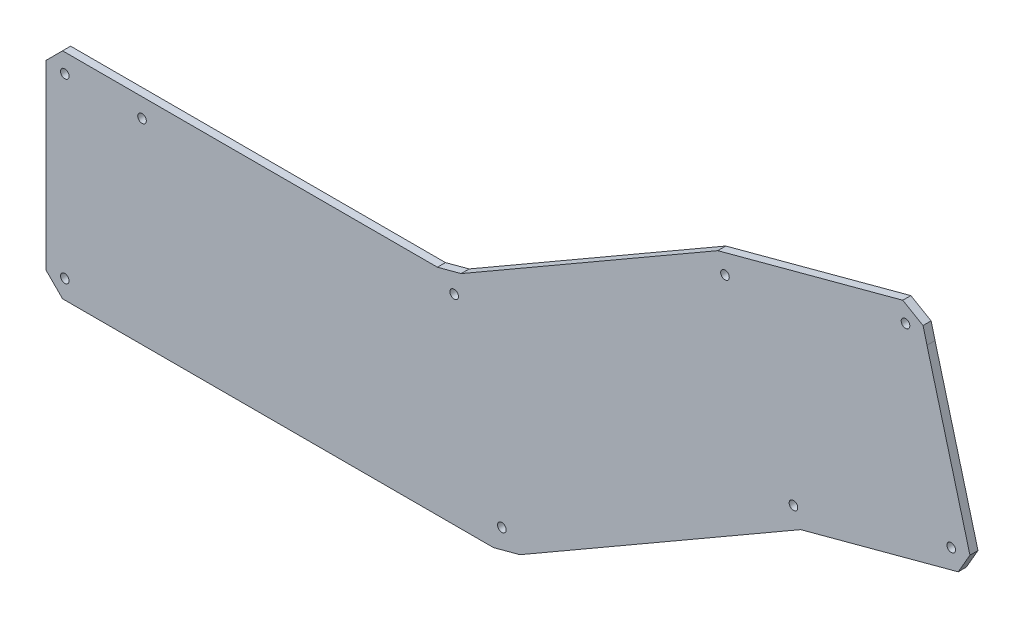
SolidWorks part; units mm, degrees
ref_plane "Plan de face" through (0, 0, 0) normal (0, 0, 1) x (1, 0, 0)
ref_plane "Plan de dessus" through (0, 0, 0) normal (0, 1, 0) x (1, 0, 0)
ref_plane "Plan de droite" through (0, 0, 0) normal (1, 0, 0) x (0, 0, -1)
sketch "Esquisse1" plane through (0, 0, 0) normal (0, 0, 1) x (1, 0, 0)
  line L0 (-73.9886, 18.0851) -> (-59.9886, 18.0851) construction
  line L1 (-73.9886, 37.0851) -> (-59.9886, 37.0851) construction
  line L2 (-73.9886, 37.0851) -> (-73.9886, 23.0851) construction
  line L3 (-73.9886, 23.0851) -> (-59.9886, 23.0851) construction
  line L4 (-59.9886, 37.0851) -> (-59.9886, 23.0851) construction
  line L5 (-73.9886, 18.0851) -> (-73.9886, 4.0851) construction
  line L6 (-73.9886, 4.0851) -> (-59.9886, 4.0851) construction
  line L7 (-59.9886, 18.0851) -> (-59.9886, 4.0851) construction
  line L8 (-73.9886, -0.9149) -> (-59.9886, -0.9149) construction
  line L9 (-73.9886, -0.9149) -> (-73.9886, -14.9149) construction
  line L10 (-73.9886, -14.9149) -> (-59.9886, -14.9149) construction
  line L11 (-59.9886, -0.9149) -> (-59.9886, -14.9149) construction
  line L12 (-73.9886, 37.0851) -> (-73.9886, 18.0851) construction
  line L13 (-54.9886, 18.0851) -> (-40.9886, 18.0851) construction
  line L14 (-54.9886, 37.0851) -> (-40.9886, 37.0851) construction
  line L15 (-54.9886, 37.0851) -> (-54.9886, 23.0851) construction
  line L16 (-54.9886, 23.0851) -> (-40.9886, 23.0851) construction
  line L17 (-40.9886, 37.0851) -> (-40.9886, 23.0851) construction
  line L18 (-54.9886, 18.0851) -> (-54.9886, 4.0851) construction
  line L19 (-54.9886, 4.0851) -> (-40.9886, 4.0851) construction
  line L20 (-40.9886, 18.0851) -> (-40.9886, 4.0851) construction
  line L21 (-54.9886, -0.9149) -> (-40.9886, -0.9149) construction
  line L22 (-54.9886, -0.9149) -> (-54.9886, -14.9149) construction
  line L23 (-54.9886, -14.9149) -> (-40.9886, -14.9149) construction
  line L24 (-40.9886, -0.9149) -> (-40.9886, -14.9149) construction
  line L25 (-54.9886, 37.0851) -> (-54.9886, 18.0851) construction
  line L26 (-35.9886, 18.0851) -> (-21.9886, 18.0851) construction
  line L27 (-35.9886, 37.0851) -> (-21.9886, 37.0851) construction
  line L28 (-35.9886, 37.0851) -> (-35.9886, 23.0851) construction
  line L29 (-35.9886, 23.0851) -> (-21.9886, 23.0851) construction
  line L30 (-21.9886, 37.0851) -> (-21.9886, 23.0851) construction
  line L31 (-35.9886, 18.0851) -> (-35.9886, 4.0851) construction
  line L32 (-35.9886, 4.0851) -> (-21.9886, 4.0851) construction
  line L33 (-21.9886, 18.0851) -> (-21.9886, 4.0851) construction
  line L34 (-35.9886, -0.9149) -> (-21.9886, -0.9149) construction
  line L35 (-35.9886, -0.9149) -> (-35.9886, -14.9149) construction
  line L36 (-35.9886, -14.9149) -> (-21.9886, -14.9149) construction
  line L37 (-21.9886, -0.9149) -> (-21.9886, -14.9149) construction
  line L38 (-35.9886, 37.0851) -> (-35.9886, 18.0851) construction
  line L39 (-16.9886, 18.0851) -> (-2.9886, 18.0851) construction
  line L40 (-16.9886, 37.0851) -> (-2.9886, 37.0851) construction
  line L41 (-16.9886, 37.0851) -> (-16.9886, 23.0851) construction
  line L42 (-16.9886, 23.0851) -> (-2.9886, 23.0851) construction
  line L43 (-2.9886, 37.0851) -> (-2.9886, 23.0851) construction
  line L44 (-16.9886, 18.0851) -> (-16.9886, 4.0851) construction
  line L45 (-16.9886, 4.0851) -> (-2.9886, 4.0851) construction
  line L46 (-2.9886, 18.0851) -> (-2.9886, 4.0851) construction
  line L47 (-16.9886, -0.9149) -> (-2.9886, -0.9149) construction
  line L48 (-16.9886, -0.9149) -> (-16.9886, -14.9149) construction
  line L49 (-16.9886, -14.9149) -> (-2.9886, -14.9149) construction
  line L50 (-2.9886, -0.9149) -> (-2.9886, -14.9149) construction
  line L51 (-16.9886, 37.0851) -> (-16.9886, 18.0851) construction
  line L52 (2.0114, 18.0851) -> (16.0114, 18.0851) construction
  line L53 (2.0114, 37.0851) -> (16.0114, 37.0851) construction
  line L54 (2.0114, 37.0851) -> (2.0114, 23.0851) construction
  line L55 (2.0114, 23.0851) -> (16.0114, 23.0851) construction
  line L56 (16.0114, 37.0851) -> (16.0114, 23.0851) construction
  line L57 (2.0114, 18.0851) -> (2.0114, 4.0851) construction
  line L58 (2.0114, 4.0851) -> (16.0114, 4.0851) construction
  line L59 (16.0114, 18.0851) -> (16.0114, 4.0851) construction
  line L60 (2.0114, -0.9149) -> (16.0114, -0.9149) construction
  line L61 (2.0114, -0.9149) -> (2.0114, -14.9149) construction
  line L62 (2.0114, -14.9149) -> (16.0114, -14.9149) construction
  line L63 (16.0114, -0.9149) -> (16.0114, -14.9149) construction
  line L64 (2.0114, 37.0851) -> (2.0114, 18.0851) construction
  line L65 (21.0114, 18.0851) -> (35.0114, 18.0851) construction
  line L66 (21.0114, 37.0851) -> (35.0114, 37.0851) construction
  line L67 (21.0114, 37.0851) -> (21.0114, 23.0851) construction
  line L68 (21.0114, 23.0851) -> (35.0114, 23.0851) construction
  line L69 (35.0114, 37.0851) -> (35.0114, 23.0851) construction
  line L70 (21.0114, 18.0851) -> (21.0114, 4.0851) construction
  line L71 (21.0114, 4.0851) -> (35.0114, 4.0851) construction
  line L72 (35.0114, 18.0851) -> (35.0114, 4.0851) construction
  line L73 (21.0114, -0.9149) -> (35.0114, -0.9149) construction
  line L74 (21.0114, -0.9149) -> (21.0114, -14.9149) construction
  line L75 (21.0114, -14.9149) -> (35.0114, -14.9149) construction
  line L76 (35.0114, -0.9149) -> (35.0114, -14.9149) construction
  line L77 (21.0114, 37.0851) -> (21.0114, 18.0851) construction
  line L78 (40.0114, 18.0851) -> (54.0114, 18.0851) construction
  line L79 (40.0114, 37.0851) -> (54.0114, 37.0851) construction
  line L80 (40.0114, 37.0851) -> (40.0114, 23.0851) construction
  line L81 (40.0114, 23.0851) -> (54.0114, 23.0851) construction
  line L82 (54.0114, 37.0851) -> (54.0114, 23.0851) construction
  line L83 (40.0114, 18.0851) -> (40.0114, 4.0851) construction
  line L84 (40.0114, 4.0851) -> (54.0114, 4.0851) construction
  line L85 (54.0114, 18.0851) -> (54.0114, 4.0851) construction
  line L86 (40.0114, -0.9149) -> (54.0114, -0.9149) construction
  line L87 (40.0114, -0.9149) -> (40.0114, -14.9149) construction
  line L88 (40.0114, -14.9149) -> (54.0114, -14.9149) construction
  line L89 (54.0114, -0.9149) -> (54.0114, -14.9149) construction
  line L90 (40.0114, 37.0851) -> (40.0114, 18.0851) construction
  line L91 (-73.9886, 18.0851) -> (-54.9886, 18.0851) construction
  line L92 (56.0114, 20.0851) -> (56.7532, 18.8002) construction
  line L93 (38.0114, 39.0851) -> (56.0114, 39.0851) construction
  line L94 (56.0114, 39.0851) -> (56.0114, 21.0851) construction
  line L95 (38.0114, 21.0851) -> (56.0114, 21.0851) construction
  line L96 (38.0114, 39.0851) -> (38.0114, 21.0851) construction
  line L97 (19.0114, 39.0851) -> (37.0114, 39.0851) construction
  line L98 (37.0114, 39.0851) -> (37.0114, 21.0851) construction
  line L99 (19.0114, 21.0851) -> (37.0114, 21.0851) construction
  line L100 (19.0114, 39.0851) -> (19.0114, 21.0851) construction
  line L101 (79.4363, 55.512) -> (88.4363, 39.9235) construction
  line L102 (88.4363, 39.9235) -> (72.8478, 30.9235) construction
  line L103 (63.8478, 46.512) -> (72.8478, 30.9235) construction
  line L104 (79.4363, 55.512) -> (63.8478, 46.512) construction
  line L105 (62.9818, 46.012) -> (71.9818, 30.4235) construction
  line L106 (71.9818, 30.4235) -> (56.3933, 21.4235) construction
  line L107 (47.3933, 37.012) -> (56.3933, 21.4235) construction
  line L108 (62.9818, 46.012) -> (47.3933, 37.012) construction
  line L109 (164.2542, 60.603) -> (148.6657, 51.603) construction
  line L110 (62.2497, 43.2799) -> (71.7497, 26.8254) construction
  line L111 (78.7042, 52.7799) -> (88.2042, 36.3254) construction
  line L112 (95.1587, 62.2799) -> (104.6587, 45.8254) construction
  line L113 (111.6132, 71.7799) -> (121.1132, 55.3254) construction
  line L114 (128.0677, 81.2799) -> (137.5677, 64.8254) construction
  line L115 (144.5221, 90.7799) -> (154.0221, 74.3254) construction
  line L116 (148.6657, 51.603) -> (157.6657, 36.0146) construction
  line L117 (69.1254, 3.371) -> (76.1254, -8.7534) construction
  line L118 (88.2497, -1.7534) -> (76.1254, -8.7534) construction
  line L119 (81.2497, 10.371) -> (88.2497, -1.7534) construction
  line L120 (81.2497, 10.371) -> (69.1254, 3.371) construction
  line L121 (59.6254, 19.8254) -> (66.6254, 7.7011) construction
  line L122 (78.7497, 14.7011) -> (66.6254, 7.7011) construction
  line L123 (71.7497, 26.8254) -> (78.7497, 14.7011) construction
  line L124 (50.1254, 36.2799) -> (57.1254, 24.1556) construction
  line L125 (69.2497, 31.1556) -> (57.1254, 24.1556) construction
  line L126 (62.2497, 43.2799) -> (69.2497, 31.1556) construction
  line L127 (62.2497, 43.2799) -> (50.1254, 36.2799) construction
  line L128 (71.7497, 26.8254) -> (59.6254, 19.8254) construction
  line L129 (85.5799, 12.871) -> (92.5799, 0.7466) construction
  line L130 (104.7042, 7.7466) -> (92.5799, 0.7466) construction
  line L131 (97.7042, 19.871) -> (104.7042, 7.7466) construction
  line L132 (97.7042, 19.871) -> (85.5799, 12.871) construction
  line L133 (76.0799, 29.3254) -> (83.0799, 17.2011) construction
  line L134 (95.2042, 24.2011) -> (83.0799, 17.2011) construction
  line L135 (88.2042, 36.3254) -> (95.2042, 24.2011) construction
  line L136 (66.5799, 45.7799) -> (73.5799, 33.6556) construction
  line L137 (85.7042, 40.6556) -> (73.5799, 33.6556) construction
  line L138 (78.7042, 52.7799) -> (85.7042, 40.6556) construction
  line L139 (78.7042, 52.7799) -> (66.5799, 45.7799) construction
  line L140 (88.2042, 36.3254) -> (76.0799, 29.3254) construction
  line L141 (102.0343, 22.371) -> (109.0343, 10.2466) construction
  line L142 (121.1587, 17.2466) -> (109.0343, 10.2466) construction
  line L143 (114.1587, 29.371) -> (121.1587, 17.2466) construction
  line L144 (114.1587, 29.371) -> (102.0343, 22.371) construction
  line L145 (92.5343, 38.8254) -> (99.5343, 26.7011) construction
  line L146 (111.6587, 33.7011) -> (99.5343, 26.7011) construction
  line L147 (104.6587, 45.8254) -> (111.6587, 33.7011) construction
  line L148 (83.0343, 55.2799) -> (90.0343, 43.1556) construction
  line L149 (102.1587, 50.1556) -> (90.0343, 43.1556) construction
  line L150 (95.1587, 62.2799) -> (102.1587, 50.1556) construction
  line L151 (95.1587, 62.2799) -> (83.0343, 55.2799) construction
  line L152 (104.6587, 45.8254) -> (92.5343, 38.8254) construction
  line L153 (118.4888, 31.871) -> (125.4888, 19.7466) construction
  line L154 (137.6132, 26.7466) -> (125.4888, 19.7466) construction
  line L155 (130.6132, 38.871) -> (137.6132, 26.7466) construction
  line L156 (130.6132, 38.871) -> (118.4888, 31.871) construction
  line L157 (108.9888, 48.3254) -> (115.9888, 36.2011) construction
  line L158 (128.1132, 43.2011) -> (115.9888, 36.2011) construction
  line L159 (121.1132, 55.3254) -> (128.1132, 43.2011) construction
  line L160 (99.4888, 64.7799) -> (106.4888, 52.6556) construction
  line L161 (118.6132, 59.6556) -> (106.4888, 52.6556) construction
  line L162 (111.6132, 71.7799) -> (118.6132, 59.6556) construction
  line L163 (111.6132, 71.7799) -> (99.4888, 64.7799) construction
  line L164 (121.1132, 55.3254) -> (108.9888, 48.3254) construction
  line L165 (134.9433, 41.371) -> (141.9433, 29.2466) construction
  line L166 (154.0677, 36.2466) -> (141.9433, 29.2466) construction
  line L167 (147.0677, 48.371) -> (154.0677, 36.2466) construction
  line L168 (147.0677, 48.371) -> (134.9433, 41.371) construction
  line L169 (125.4433, 57.8254) -> (132.4433, 45.7011) construction
  line L170 (144.5677, 52.7011) -> (132.4433, 45.7011) construction
  line L171 (137.5677, 64.8254) -> (144.5677, 52.7011) construction
  line L172 (115.9433, 74.2799) -> (122.9433, 62.1556) construction
  line L173 (135.0677, 69.1556) -> (122.9433, 62.1556) construction
  line L174 (128.0677, 81.2799) -> (135.0677, 69.1556) construction
  line L175 (128.0677, 81.2799) -> (115.9433, 74.2799) construction
  line L176 (137.5677, 64.8254) -> (125.4433, 57.8254) construction
  line L177 (151.3978, 50.871) -> (158.3978, 38.7466) construction
  line L178 (170.5221, 45.7466) -> (158.3978, 38.7466) construction
  line L179 (163.5221, 57.871) -> (170.5221, 45.7466) construction
  line L180 (163.5221, 57.871) -> (151.3978, 50.871) construction
  line L181 (141.8978, 67.3254) -> (148.8978, 55.2011) construction
  line L182 (161.0221, 62.2011) -> (148.8978, 55.2011) construction
  line L183 (154.0221, 74.3254) -> (161.0221, 62.2011) construction
  line L184 (132.3978, 83.7799) -> (139.3978, 71.6556) construction
  line L185 (151.5221, 78.6556) -> (139.3978, 71.6556) construction
  line L186 (144.5221, 90.7799) -> (151.5221, 78.6556) construction
  line L187 (144.5221, 90.7799) -> (132.3978, 83.7799) construction
  line L188 (154.0221, 74.3254) -> (141.8978, 67.3254) construction
  line L189 (173.2542, 45.0146) -> (157.6657, 36.0146) construction
  line L190 (164.2542, 60.603) -> (173.2542, 45.0146) construction
  line L191 (178.3169, 34.0986) -> (169.0534, 56.4627) construction
  line L192 (169.5193, 62.7839) -> (174.1781, 45.3972) construction
  line L193 (174.1781, 45.3972) -> (191.5647, 50.056) construction
  line L194 (186.906, 67.4426) -> (191.5647, 50.056) construction
  line L195 (162.1337, 98.0749) -> (167.0513, 79.7223) construction
  line L196 (169.5193, 62.7839) -> (186.906, 67.4426) construction
  line L197 (167.0513, 79.7223) -> (180.5742, 83.3457) construction
  line L198 (162.1337, 98.0749) -> (175.6567, 101.6983) construction
  line L199 (162.1337, 98.0749) -> (165.7572, 84.5519) construction
  line L200 (165.7572, 84.5519) -> (179.2801, 88.1754) construction
  line L201 (175.6567, 101.6983) -> (179.2801, 88.1754) construction
  line L202 (167.0513, 79.7223) -> (170.6747, 66.1993) construction
  line L203 (170.6747, 66.1993) -> (184.1977, 69.8228) construction
  line L204 (180.5742, 83.3457) -> (184.1977, 69.8228) construction
  line L205 (171.9688, 61.3697) -> (185.4918, 64.9932) construction
  line L206 (171.9688, 61.3697) -> (175.5923, 47.8467) construction
  line L207 (175.5923, 47.8467) -> (189.1152, 51.4702) construction
  line L208 (185.4918, 64.9932) -> (189.1152, 51.4702) construction
  line L209 (185.4038, 84.6398) -> (198.9268, 88.2633) construction
  line L210 (180.4863, 102.9924) -> (194.0092, 106.6159) construction
  line L211 (180.4863, 102.9924) -> (184.1097, 89.4695) construction
  line L212 (184.1097, 89.4695) -> (197.6327, 93.0929) construction
  line L213 (194.0092, 106.6159) -> (197.6327, 93.0929) construction
  line L214 (185.4038, 84.6398) -> (189.0273, 71.1169) construction
  line L215 (189.0273, 71.1169) -> (202.5503, 74.7403) construction
  line L216 (198.9268, 88.2633) -> (202.5503, 74.7403) construction
  line L217 (190.3214, 66.2873) -> (203.8444, 69.9107) construction
  line L218 (190.3214, 66.2873) -> (193.9449, 52.7643) construction
  line L219 (193.9449, 52.7643) -> (207.4678, 56.3878) construction
  line L220 (203.8444, 69.9107) -> (207.4678, 56.3878) construction
  line L221 (187.8719, 67.7015) -> (192.5307, 50.3148) construction
  line L222 (192.5307, 50.3148) -> (209.9173, 54.9735) construction
  line L223 (205.2586, 72.3602) -> (209.9173, 54.9735) construction
  line L224 (180.4863, 102.9924) -> (185.4038, 84.6398) construction
  line L225 (187.8719, 67.7015) -> (205.2586, 72.3602) construction
  line L226 (203.7564, 89.5574) -> (217.2794, 93.1809) construction
  line L227 (198.8389, 107.91) -> (212.3618, 111.5335) construction
  line L228 (198.8389, 107.91) -> (202.4623, 94.387) construction
  line L229 (202.4623, 94.387) -> (215.9853, 98.0105) construction
  line L230 (212.3618, 111.5335) -> (215.9853, 98.0105) construction
  line L231 (203.7564, 89.5574) -> (207.3799, 76.0344) construction
  line L232 (207.3799, 76.0344) -> (220.9029, 79.6579) construction
  line L233 (217.2794, 93.1809) -> (220.9029, 79.6579) construction
  line L234 (208.674, 71.2048) -> (222.197, 74.8283) construction
  line L235 (208.674, 71.2048) -> (212.2975, 57.6819) construction
  line L236 (212.2975, 57.6819) -> (225.8204, 61.3053) construction
  line L237 (222.197, 74.8283) -> (225.8204, 61.3053) construction
  line L238 (206.2245, 72.619) -> (210.8833, 55.2324) construction
  line L239 (210.8833, 55.2324) -> (228.2699, 59.8911) construction
  line L240 (223.6112, 77.2778) -> (228.2699, 59.8911) construction
  line L241 (198.8389, 107.91) -> (203.7564, 89.5574) construction
  line L242 (206.2245, 72.619) -> (223.6112, 77.2778) construction
  line L243 (167.0513, 79.7223) -> (185.4038, 84.6398) construction
  line L244 (38.0114, 20.0851) -> (56.0114, 20.0851) construction
  line L245 (56.0114, 20.0851) -> (56.0114, 2.0851) construction
  line L246 (38.0114, 2.0851) -> (56.0114, 2.0851) construction
  line L247 (38.0114, 20.0851) -> (38.0114, 2.0851) construction
  line L248 (72.4818, 29.5575) -> (56.8933, 20.5575) construction
  line L249 (56.8933, 20.5575) -> (65.8933, 4.969) construction
  line L250 (81.4818, 13.969) -> (65.8933, 4.969) construction
  line L251 (72.4818, 29.5575) -> (81.4818, 13.969) construction
  line L252 (56.8933, 20.5575) -> (57.6111, 19.3142) construction
  line L253 (164.6018, 81.1365) -> (169.2605, 63.7498) construction
  line L254 (169.2605, 63.7498) -> (186.6472, 68.4086) construction
  line L255 (181.9884, 85.7952) -> (186.6472, 68.4086) construction
  line L256 (164.6018, 81.1365) -> (181.9884, 85.7952) construction
  line L257 (154.7542, 77.0575) -> (163.7542, 61.469) construction
  line L258 (163.7542, 61.469) -> (148.1657, 52.469) construction
  line L259 (139.1657, 68.0575) -> (148.1657, 52.469) construction
  line L260 (154.7542, 77.0575) -> (139.1657, 68.0575) construction
  line L261 (196.3894, 109.3242) -> (213.776, 113.983) construction
  line L262 (-94.7538, 35.7952) -> (-76.7538, 35.7952) construction
  line L263 (-94.7538, 35.7952) -> (-94.7538, 2.7952) construction
  line L264 (-94.7538, 2.7952) -> (-76.7538, 2.7952) construction
  line L265 (-76.7538, 35.7952) -> (-76.7538, 2.7952) construction
  line L266 (213.776, 113.983) -> (218.4348, 96.5963) construction
  line L267 (201.0481, 91.9375) -> (218.4348, 96.5963) construction
  line L268 (196.3894, 109.3242) -> (201.0481, 91.9375) construction
  line L269 (-75.9886, -16.9149) -> (-57.9886, -16.9149) construction
  line L270 (-57.9886, 1.0851) -> (-57.9886, -16.9149) construction
  line L271 (-75.9886, 1.0851) -> (-57.9886, 1.0851) construction
  line L272 (-75.9886, 1.0851) -> (-75.9886, -16.9149) construction
  line L273 (38.0114, -16.9149) -> (56.0114, -16.9149) construction
  line L274 (56.0114, 1.0851) -> (56.0114, -16.9149) construction
  line L275 (38.0114, 1.0851) -> (56.0114, 1.0851) construction
  line L276 (38.0114, 1.0851) -> (38.0114, -16.9149) construction
  line L277 (-75.9886, 39.0851) -> (-57.9886, 39.0851) construction
  line L278 (-57.9886, 39.0851) -> (-57.9886, 21.0851) construction
  line L279 (-75.9886, 21.0851) -> (-57.9886, 21.0851) construction
  line L280 (-75.9886, 39.0851) -> (-75.9886, 21.0851) construction
  line L281 (145.2542, 93.512) -> (129.6657, 84.512) construction
  line L282 (129.6657, 84.512) -> (138.6657, 68.9235) construction
  line L283 (154.2542, 77.9235) -> (138.6657, 68.9235) construction
  line L284 (145.2542, 93.512) -> (154.2542, 77.9235) construction
  line L285 (223.4353, 116.5711) -> (228.0941, 99.1845) construction
  line L286 (148.2159, 106.7689) -> (211.1879, 123.6422) construction
  line L287 (177.5508, 35.9482) -> (235.6877, 51.5259) construction
  line L288 (177.5508, 35.9482) -> (72.9989, -24.4149) construction
  line L289 (-95.7538, -26.9149) -> (63.6687, -26.9149) construction
  line L290 (-100.7538, 35.7952) -> (-100.7538, -21.9149) construction
  line L291 (-75.9886, 49.0851) -> (43.3046, 49.0851) construction
  line L292 (148.2159, 106.7689) -> (52.6347, 51.5851) construction
  line L293 (-75.9886, 49.0851) -> (-57.9886, 49.0851) construction
  line L294 (140.2542, 102.1722) -> (124.6657, 93.1722) construction
  line L295 (193.8012, 118.9835) -> (211.1879, 123.6422) construction
  line L296 (213.4714, 45.5731) -> (230.8581, 50.2318) construction
  line L297 (38.0114, -26.9149) -> (38.0114, -85.4624) construction
  line L298 (178.2542, 36.3543) -> (162.6657, 27.3543) construction
  line L299 (38.0114, -26.9149) -> (56.0114, -26.9149) construction
  line L300 (-100.7538, 2.7952) -> (-100.7538, -38.0419) construction
  line L301 (-100.7538, 35.7952) -> (-100.7538, 2.7952) construction
  line L302 (-75.9886, 49.0851) -> (-95.7538, 49.0851) construction
  line L303 (-100.7538, 44.0851) -> (-100.7538, 35.7952) construction
  line L304 (211.1879, 123.6422) -> (216.0732, 124.9512) construction
  line L305 (222.1691, 121.4083) -> (223.4353, 116.5711) construction
  line L306 (228.0941, 99.1845) -> (239.2233, 57.6497) construction
  line L307 (216.0732, 124.9512) -> (222.1691, 121.4083) construction
  line L308 (235.6877, 51.5259) -> (239.2233, 57.6497) construction
  line L309 (63.6687, -26.9149) -> (72.9989, -24.4149) construction
  line L310 (52.6347, 51.5851) -> (43.3046, 49.0851) construction
  line L311 (-95.7538, 49.0851) -> (-100.7538, 44.0851) construction
  line L312 (-100.7538, -21.9149) -> (-95.7538, -26.9149) construction
  line L313 (-95.7538, 49.0851) -> (-95.7538, 44.0851) construction
  line L314 (-95.7538, 44.0851) -> (-100.7538, 44.0851) construction
  line L315 (-95.7538, -26.9149) -> (-95.7538, -21.9149) construction
  line L316 (68.3338, -25.6649) -> (67.0397, -20.8353) construction
  line L317 (47.9697, 50.3351) -> (49.2637, 45.5055) construction
  line L318 (177.5508, 35.9482) -> (175.6374, 40.5676) construction
  line L319 (148.2159, 106.7689) -> (150.1293, 102.1495) construction
  line L320 (239.2233, 57.6497) -> (234.3936, 56.3556) construction
  line L321 (216.0732, 124.9512) -> (217.3634, 120.1206) construction
  line L322 (-75.9886, 51.0851) -> (43.0413, 51.0851) construction
  line L323 (51.8627, 53.4488) -> (43.0413, 51.0851) construction
  line L324 (147.4439, 108.6326) -> (51.8627, 53.4488) construction
  line L325 (147.4439, 108.6326) -> (210.6702, 125.5741) construction
  line L326 (210.6702, 125.5741) -> (216.3591, 127.0984) construction
  line L327 (216.3591, 127.0984) -> (223.8932, 122.7195) construction
  line L328 (223.8932, 122.7195) -> (225.3687, 117.0832) construction
  line L329 (225.3687, 117.0832) -> (230.0259, 99.7021) construction
  line L330 (230.0259, 99.7021) -> (241.3695, 57.3671) construction
  line L331 (237.0056, 49.8085) -> (241.3695, 57.3671) construction
  line L332 (178.3228, 34.0845) -> (237.0056, 49.8085) construction
  line L333 (178.3228, 34.0845) -> (73.7708, -26.2786) construction
  line L334 (63.932, -28.9149) -> (73.7708, -26.2786) construction
  line L335 (-96.5822, -28.9149) -> (63.932, -28.9149) construction
  line L336 (-102.7538, -22.7433) -> (-96.5822, -28.9149) construction
  line L337 (-102.7538, 35.7952) -> (-102.7538, -22.7433) construction
  line L338 (-102.7538, 44.9135) -> (-102.7538, 35.7952) construction
  line L339 (-96.5822, 51.0851) -> (-102.7538, 44.9135) construction
  line L340 (-75.9886, 51.0851) -> (-76.7538, 51.0851) construction
  line L341 (2.0114, 40.0851) -> (52.7161, 40.0851) construction
  line L342 (151.6898, 98.3823) -> (50.7161, 40.0851) construction
  line L343 (-100.7538, 35.7952) -> (-100.7538, -17.9149) construction
  line L344 (-100.7538, -17.9149) -> (66.2572, -17.9149) construction
  line L345 (174.0769, 44.3349) -> (66.2572, -17.9149) construction
  line L346 (174.0769, 44.3349) -> (229.4947, 59.184) construction
  line L347 (214.4832, 115.2077) -> (229.4947, 59.184) construction
  line L348 (151.6898, 98.3823) -> (214.4832, 115.2077) construction
  line L349 (225.0947, 75.6047) -> (228.7182, 62.0818) construction
  line L350 (176.3687, 44.949) -> (189.8917, 48.5724) construction
  line L351 (89.7497, -4.3515) -> (77.6254, -11.3515) construction
  line L352 (-54.9886, -17.9149) -> (-40.9886, -17.9149) construction
  line L353 (-100.7538, 35.7952) -> (-100.7538, 2.7952) construction
  line L354 (2.0114, 40.0851) -> (16.0114, 40.0851) construction
  line L355 (77.2042, 55.378) -> (65.0799, 48.378) construction
  line L356 (179.7098, 105.8902) -> (193.2328, 109.5137) construction
  line L357 (2.0114, 40.0851) -> (-100.7538, 40.0851) construction
  line L358 (-95.7538, 44.0851) -> (-60.6491, 44.0851) construction
  line L359 (-100.7538, 35.7952) -> (-100.7538, 40.0851) construction
  line L360 (-75.9886, 49.5851) -> (43.2388, 49.5851) construction
  line L361 (52.4417, 52.051) -> (43.2388, 49.5851) construction
  line L362 (-76.7538, 51.0851) -> (-96.5822, 51.0851) construction
  line L363 (-66.9886, 37.0851) -> (-66.9886, 51.0851) construction
  line L364 (-75.9886, 51.0851) -> (-96.5822, 51.0851) construction
  line L365 (148.0229, 107.2348) -> (52.4417, 52.051) construction
  line L366 (-76.7538, 39.0851) -> (-97.0101, 39.0851) construction
  line L367 (-76.7538, 39.0851) -> (-76.7538, 1.0851) construction
  line L368 (-76.7538, 1.0851) -> (-97.0101, 1.0851) construction
  line L369 (-97.0101, 39.0851) -> (-97.0101, 1.0851) construction
  line L370 (148.0229, 107.2348) -> (211.0584, 124.1252) construction
  line L371 (211.0584, 124.1252) -> (216.1447, 125.488) construction
  line L372 (216.1447, 125.488) -> (222.6001, 121.7361) construction
  line L373 (222.6001, 121.7361) -> (223.9186, 116.6992) construction
  line L374 (223.9186, 116.6992) -> (228.577, 99.3139) construction
  line L375 (228.577, 99.3139) -> (239.7598, 57.579) construction
  line L376 (236.0172, 51.0966) -> (239.7598, 57.579) construction
  line L377 (177.7438, 35.4823) -> (236.0172, 51.0966) construction
  line L378 (177.7438, 35.4823) -> (73.1918, -24.8808) construction
  line L379 (63.7346, -27.4149) -> (73.1918, -24.8808) construction
  line L380 (-95.9609, -27.4149) -> (63.7346, -27.4149) construction
  line L381 (-101.2538, -22.122) -> (-95.9609, -27.4149) construction
  line L382 (-101.2538, 35.7952) -> (-101.2538, -22.122) construction
  line L383 (-101.2538, 44.2922) -> (-101.2538, 35.7952) construction
  line L384 (-95.9609, 49.5851) -> (-101.2538, 44.2922) construction
  line L385 (-76.7538, 49.5851) -> (-95.9609, 49.5851) construction
  line L386 (-75.9886, 49.5851) -> (-76.7538, 49.5851) construction
  line L387 (-76.7538, 49.0851) -> (-95.7538, 49.0851) construction
  line L388 (-95.7538, 49.0851) -> (-100.7538, 44.0851) construction
  line L389 (-100.7538, 44.0851) -> (-100.7538, 35.7952) construction
  line L390 (-100.7538, 35.7952) -> (-100.7538, -21.9149) construction
  line L391 (-100.7538, -21.9149) -> (-95.7538, -26.9149) construction
  line L392 (-95.7538, -26.9149) -> (63.6687, -26.9149) construction
  line L393 (63.6687, -26.9149) -> (72.9989, -24.4149) construction
  line L394 (177.5508, 35.9482) -> (72.9989, -24.4149) construction
  line L395 (177.5508, 35.9482) -> (235.6877, 51.5259) construction
  line L396 (235.6877, 51.5259) -> (239.2233, 57.6497) construction
  line L397 (228.0941, 99.1845) -> (239.2233, 57.6497) construction
  line L398 (223.4353, 116.5711) -> (228.0941, 99.1845) construction
  line L399 (222.1691, 121.4083) -> (223.4353, 116.5711) construction
  line L400 (216.0732, 124.9512) -> (222.1691, 121.4083) construction
  line L401 (211.1879, 123.6422) -> (216.0732, 124.9512) construction
  line L402 (148.2159, 106.7689) -> (211.1879, 123.6422) construction
  line L403 (148.2159, 106.7689) -> (52.6347, 51.5851) construction
  line L404 (52.6347, 51.5851) -> (43.3046, 49.0851) construction
  line L405 (-75.9886, 49.0851) -> (43.3046, 49.0851) construction
  line L406 (-75.9886, 49.0851) -> (-76.7538, 49.0851) construction
  line L407 (-76.7538, 52.5851) -> (-97.2035, 52.5851) construction
  line L408 (-97.2035, 52.5851) -> (-104.2538, 45.5349) construction
  line L409 (-104.2538, 45.5349) -> (-104.2538, 35.7952) construction
  line L410 (-104.2538, 35.7952) -> (-104.2538, -23.3646) construction
  line L411 (-104.2538, -23.3646) -> (-97.2035, -30.4149) construction
  line L412 (-97.2035, -30.4149) -> (64.1295, -30.4149) construction
  line L413 (64.1295, -30.4149) -> (74.3498, -27.6764) construction
  line L414 (178.9017, 32.6867) -> (74.3498, -27.6764) construction
  line L415 (178.9017, 32.6867) -> (237.994, 48.5204) construction
  line L416 (237.994, 48.5204) -> (242.9792, 57.1552) construction
  line L417 (231.4748, 100.0903) -> (242.9792, 57.1552) construction
  line L418 (226.8187, 117.4673) -> (231.4748, 100.0903) construction
  line L419 (225.1863, 123.7029) -> (226.8187, 117.4673) construction
  line L420 (216.5734, 128.7087) -> (225.1863, 123.7029) construction
  line L421 (210.282, 127.023) -> (216.5734, 128.7087) construction
  line L422 (146.8649, 110.0304) -> (210.282, 127.023) construction
  line L423 (146.8649, 110.0304) -> (51.2838, 54.8466) construction
  line L424 (51.2838, 54.8466) -> (42.8438, 52.5851) construction
  line L425 (-75.9886, 52.5851) -> (42.8438, 52.5851) construction
  line L426 (-75.9886, 52.5851) -> (-76.7538, 52.5851) construction
  line L427 (-76.7538, 51.0851) -> (-96.5822, 51.0851)
  line L428 (-96.5822, 51.0851) -> (-102.7538, 44.9135)
  line L429 (-102.7538, 44.9135) -> (-102.7538, 35.7952)
  line L430 (-102.7538, 35.7952) -> (-102.7538, -22.7433)
  line L431 (-102.7538, -22.7433) -> (-96.5822, -28.9149)
  line L432 (-96.5822, -28.9149) -> (63.932, -28.9149)
  line L433 (63.932, -28.9149) -> (73.7708, -26.2786)
  line L434 (178.3228, 34.0845) -> (73.7708, -26.2786)
  line L435 (178.3228, 34.0845) -> (237.0056, 49.8085)
  line L436 (237.0056, 49.8085) -> (241.3695, 57.3671)
  line L437 (230.0259, 99.7021) -> (241.3695, 57.3671)
  line L438 (225.3687, 117.0832) -> (230.0259, 99.7021)
  line L439 (223.8932, 122.7195) -> (225.3687, 117.0832)
  line L440 (216.3591, 127.0984) -> (223.8932, 122.7195)
  line L441 (210.6702, 125.5741) -> (216.3591, 127.0984)
  line L442 (147.4439, 108.6326) -> (210.6702, 125.5741)
  line L443 (147.4439, 108.6326) -> (51.8627, 53.4488)
  line L444 (51.8627, 53.4488) -> (43.0413, 51.0851)
  line L445 (-75.9886, 51.0851) -> (43.0413, 51.0851)
  line L446 (-75.9886, 51.0851) -> (-76.7538, 51.0851)
  circle A0 centre (-95.7538, 44.0851) radius 1.5 construction
  circle A1 centre (-95.7538, -21.9149) radius 1.5 construction
  circle A2 centre (67.0397, -20.8353) radius 1.5 construction
  circle A3 centre (49.2637, 45.5055) radius 1.5 construction
  circle A4 centre (175.6374, 40.5676) radius 1.5 construction
  circle A5 centre (150.1293, 102.1495) radius 1.5 construction
  circle A6 centre (234.3936, 56.3556) radius 1.5 construction
  circle A7 centre (217.3634, 120.1206) radius 1.5 construction
  circle A8 centre (-66.9886, 44.0851) radius 1.5 construction
  circle A9 centre (-95.7538, 44.0851) radius 1.6
  circle A10 centre (-66.9886, 44.0851) radius 1.6
  circle A11 centre (-95.7538, -21.9149) radius 1.6
  circle A12 centre (49.2637, 45.5055) radius 1.6
  circle A13 centre (67.0397, -20.8353) radius 1.6
  circle A14 centre (217.3634, 120.1206) radius 1.6
  circle A15 centre (150.1293, 102.1495) radius 1.6
  circle A16 centre (175.6374, 40.5676) radius 1.6
  circle A17 centre (234.3936, 56.3556) radius 1.6
  point P304 (48.3046, 49.0851)
  point P305 (240.5174, 52.82)
  point P308 (68.6687, -26.9149)
  point P309 (-100.7538, -26.9149)
  point P311 (-100.7538, 49.0851)
  point P312 (220.9029, 126.2453)
  dimension "D32" = 3
  dimension "D33" = 5
  dimension "D40" = 5
  dimension "D41" = 5
  dimension "D42" = 5
  dimension "D43" = 5
  dimension "D44" = 2
  dimension "D53" = 1.5
  dimension "D1" = 14
  dimension "D2" = 14
  dimension "D4" = 19
  dimension "D6" = 19
  dimension "D7" = 30
  dimension "D10" = 1
  dimension "D11" = 2
  dimension "D13" = 0.5
  dimension "D15" = 2
  dimension "D12" = 7.5
  dimension "D14" = 19
  dimension "D18" = 2
  dimension "D20" = 18
  dimension "D21" = 33
  dimension "D22" = 2
  dimension "D8" = 2
  dimension "D9" = 2
  dimension "D16" = 2
  dimension "D19" = 2
  dimension "D23" = 2
  dimension "D24" = 10
  dimension "D25" = 10
  dimension "D26" = 10
  dimension "D27" = 10
  dimension "D28" = 10
  dimension "D29" = 6
  dimension "D30" = 10
  dimension "D31" = 10
  dimension "D45" = 3
  dimension "D46" = 3
  dimension "D47" = 6
  dimension "D48" = 3
  dimension "D49" = 3
  dimension "D50" = 3
  dimension "D51" = 3
  dimension "D52" = 3
  dimension "D54" = 0.5
  dimension "D55" = 3.5
  dimension "D56" = 1.5
  dimension "D57" = 0.1
  dimension "D3" = 3
  dimension "D5" = 7
  dimension "D17" = 3
extrude "Boss.-Extru.1" add sketch "Esquisse1" along normal blind 3
